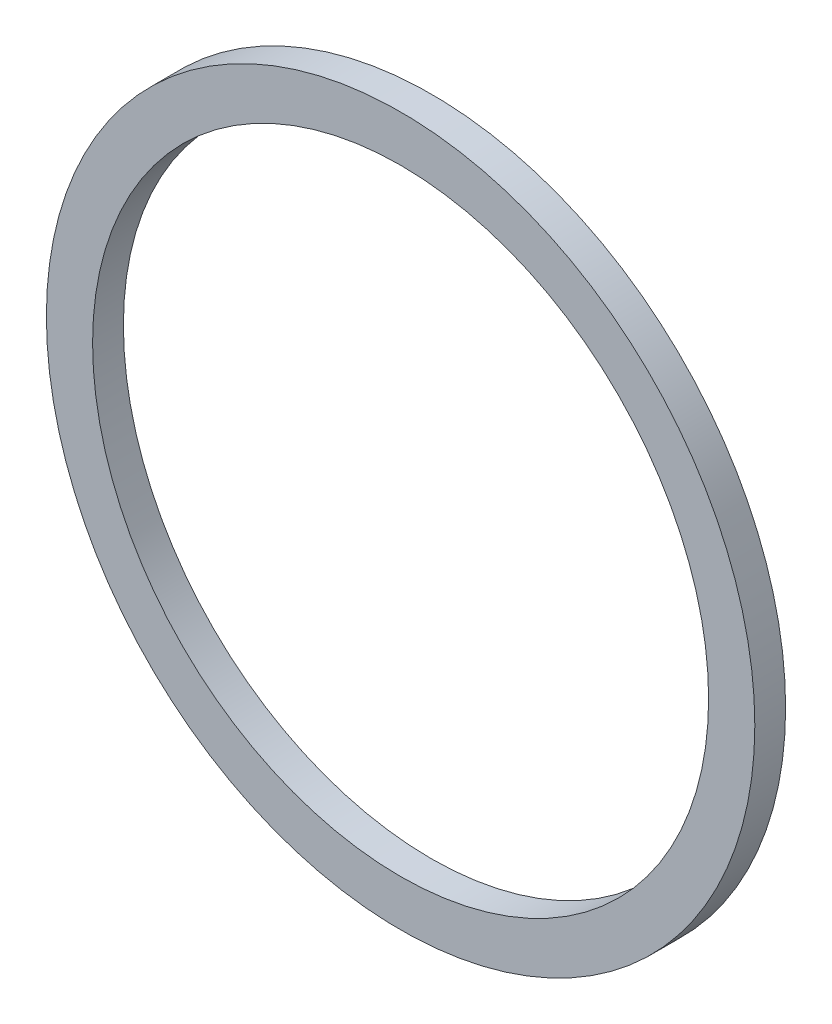
SolidWorks part; units mm, degrees
ref_plane "前视基准面" through (0, 0, 0) normal (0, 0, 1) x (1, 0, 0)
ref_plane "上视基准面" through (0, 0, 0) normal (0, 1, 0) x (1, 0, 0)
ref_plane "右视基准面" through (0, 0, 0) normal (1, 0, 0) x (0, 0, -1)
sketch "草图1" plane through (0, 0, 0) normal (0, 0, 1) x (1, 0, 0)
  circle A0 centre (0, 0) radius 11.5
  circle A1 centre (0, 0) radius 10
  dimension "D1" = 20
  dimension "D2" = 23
extrude "凸台-拉伸1" add sketch "草图1" along normal blind 1 contours A0
